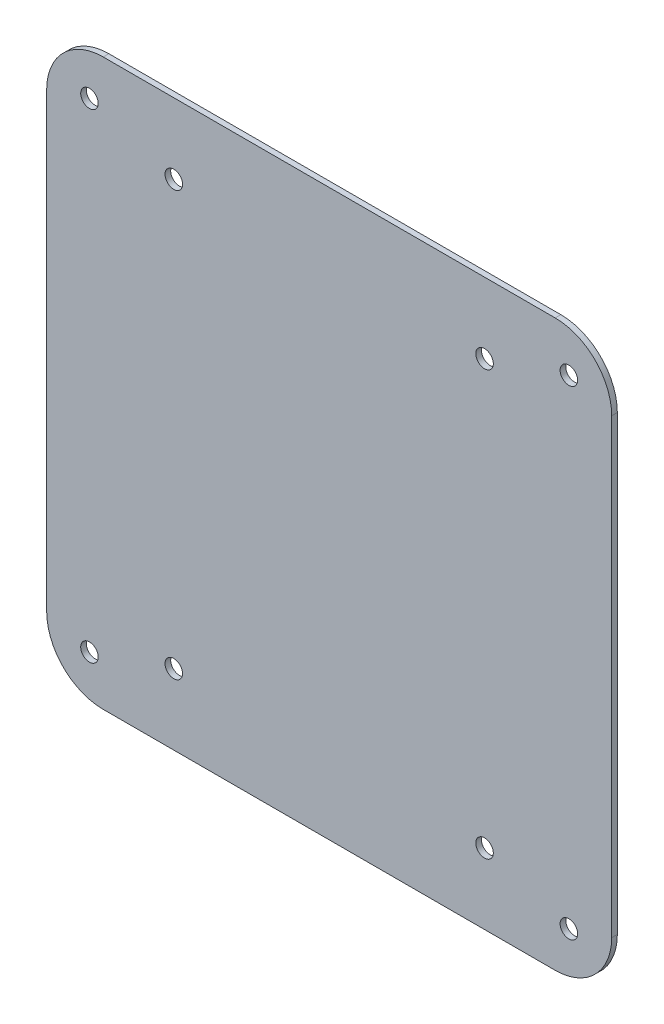
SolidWorks part; units mm, degrees
ref_plane "前视基准面" through (0, 0, 0) normal (0, 0, 1) x (1, 0, 0)
ref_plane "上视基准面" through (0, 0, 0) normal (0, 1, 0) x (1, 0, 0)
ref_plane "右视基准面" through (0, 0, 0) normal (1, 0, 0) x (0, 0, -1)
sketch "草图1" plane through (0, 0, 0) normal (0, 0, 1) x (1, 0, 0)
  line L0 (0, 50) -> (0, -50) construction
  line L5 (-40, -50) -> (40, -50)
  line L6 (-50, -40) -> (-50, 40)
  line L7 (-40, 50) -> (40, 50)
  line L8 (50, -40) -> (50, 40)
  line L9 (-50, -50) -> (50, 50) construction
  line L10 (-50, 50) -> (50, -50) construction
  line L11 (-50, 0) -> (50, 0) construction
  circle A0 centre (-27.5, 37.5) radius 1.55
  circle A1 centre (27.5, 37.5) radius 1.55
  circle A2 centre (27.5, -37.5) radius 1.55
  circle A3 centre (-27.5, -37.5) radius 1.55
  arc A4 (40, 50) -> (50, 40) centre (40, 40) cw
  arc A5 (40, -50) -> (50, -40) centre (40, -40) ccw
  arc A6 (-40, -50) -> (-50, -40) centre (-40, -40) cw
  arc A7 (-50, 40) -> (-40, 50) centre (-40, 40) cw
  circle A8 centre (-42.4264, 42.4264) radius 1.55
  circle A12 centre (42.4264, 42.4264) radius 1.55
  circle A13 centre (42.4264, -42.4264) radius 1.55
  circle A14 centre (-42.4264, -42.4264) radius 1.55
  point P0 (0, 0)
  point P10 (0, 0)
  dimension "D3" = 100
  dimension "D5" = 10
  dimension "D6" = 60
  dimension "D1" = 55
  dimension "D2" = 75
  dimension "D4" = 100
extrude "凸台-拉伸1" add sketch "草图1" along normal blind 1
